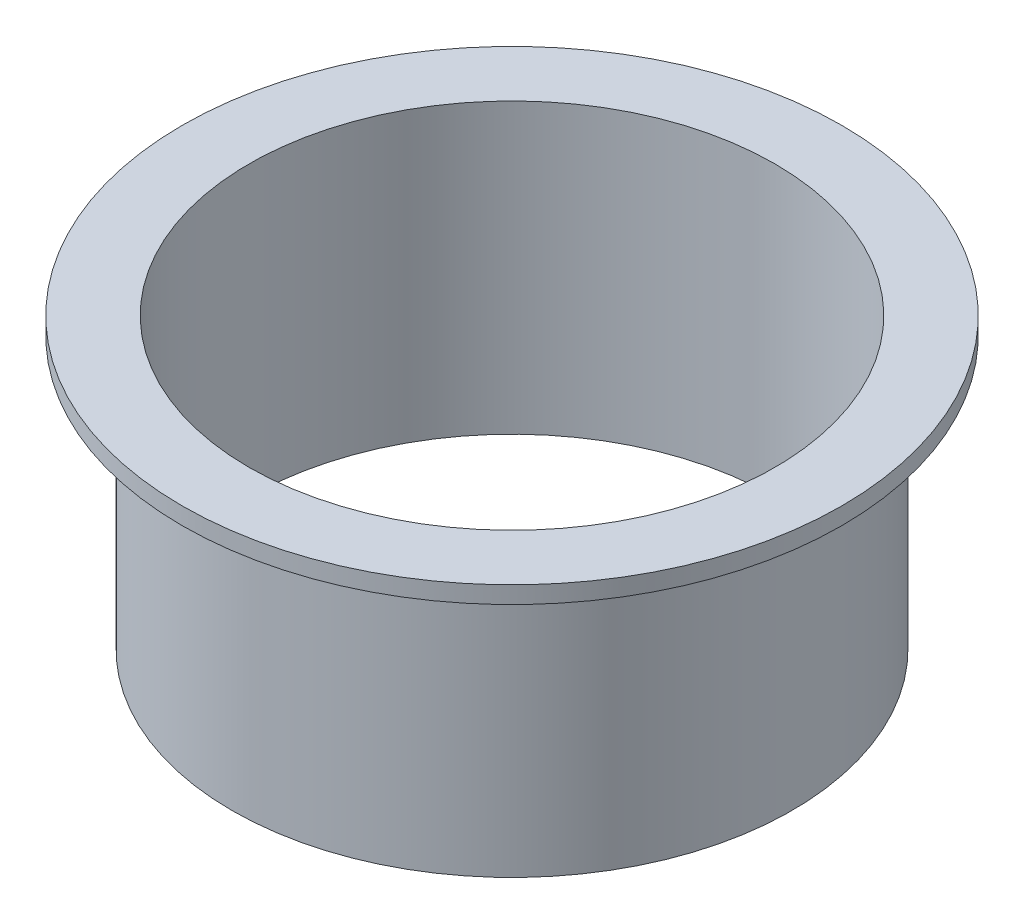
SolidWorks part; units mm, degrees
ref_plane "Front Plane" through (0, 0, 0) normal (0, 0, 1) x (1, 0, 0)
ref_plane "Top Plane" through (0, 0, 0) normal (0, 1, 0) x (1, 0, 0)
ref_plane "Right Plane" through (0, 0, 0) normal (1, 0, 0) x (0, 0, -1)
sketch "Sketch1" plane through (0, 0, 0) normal (0, 1, 0) x (1, 0, 0)
  circle A0 centre (0, 0) radius 30.7
  circle A1 centre (0, 0) radius 32.7
  dimension "D1" = 61.4
  dimension "D2" = 65.4
extrude "Boss-Extrude1" add sketch "Sketch1" along normal blind 33.7
sketch "Sketch2" plane through (0, 33.7, 0) normal (0, 1, 0) x (1, 0, 0)
  circle A0 centre (0, 0) radius 30.7
  circle A1 centre (0, 0) radius 38.5
  dimension "D1" = 77
extrude "Boss-Extrude2" add sketch "Sketch2" against normal blind 2
